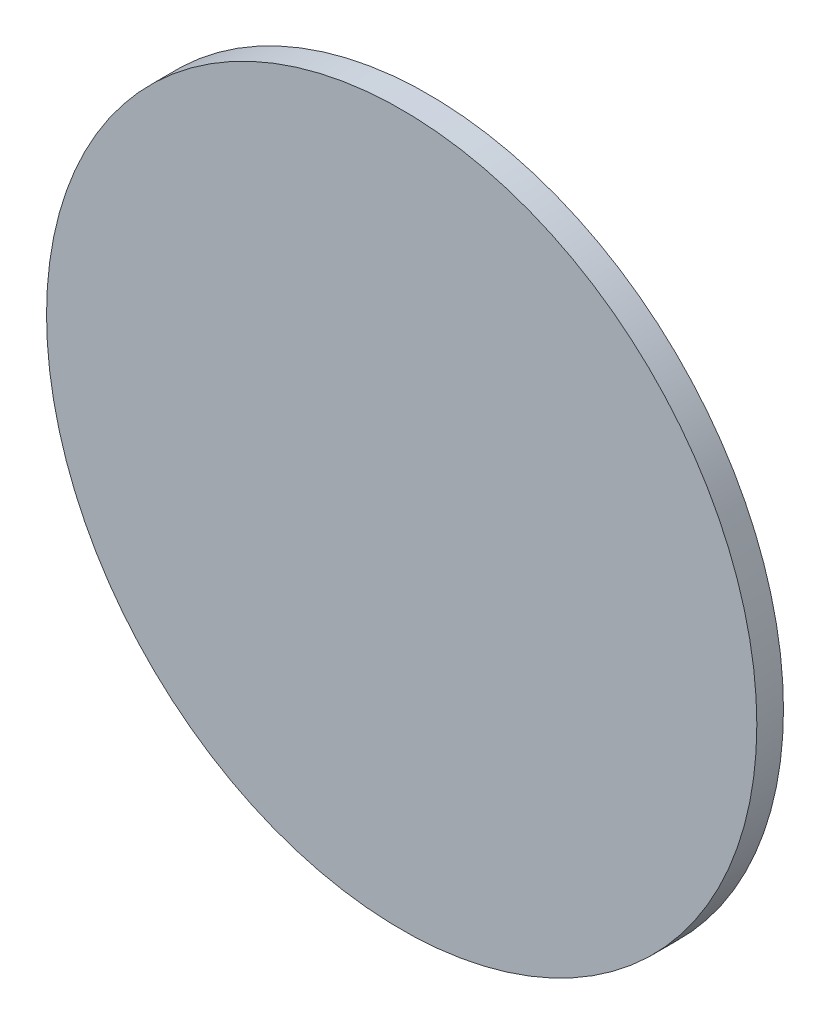
SolidWorks part; units mm, degrees
ref_plane "Plan de face" through (0, 0, 0) normal (0, 0, 1) x (1, 0, 0)
ref_plane "Plan de dessus" through (0, 0, 0) normal (0, 1, 0) x (1, 0, 0)
ref_plane "Plan de droite" through (0, 0, 0) normal (1, 0, 0) x (0, 0, -1)
sketch "Esquisse1" plane through (0, 0, 0) normal (0, 0, 1) x (1, 0, 0)
  circle A0 centre (0, 0) radius 80
extrude "Boss.-Extru.1" add sketch "Esquisse1" along normal blind 6
